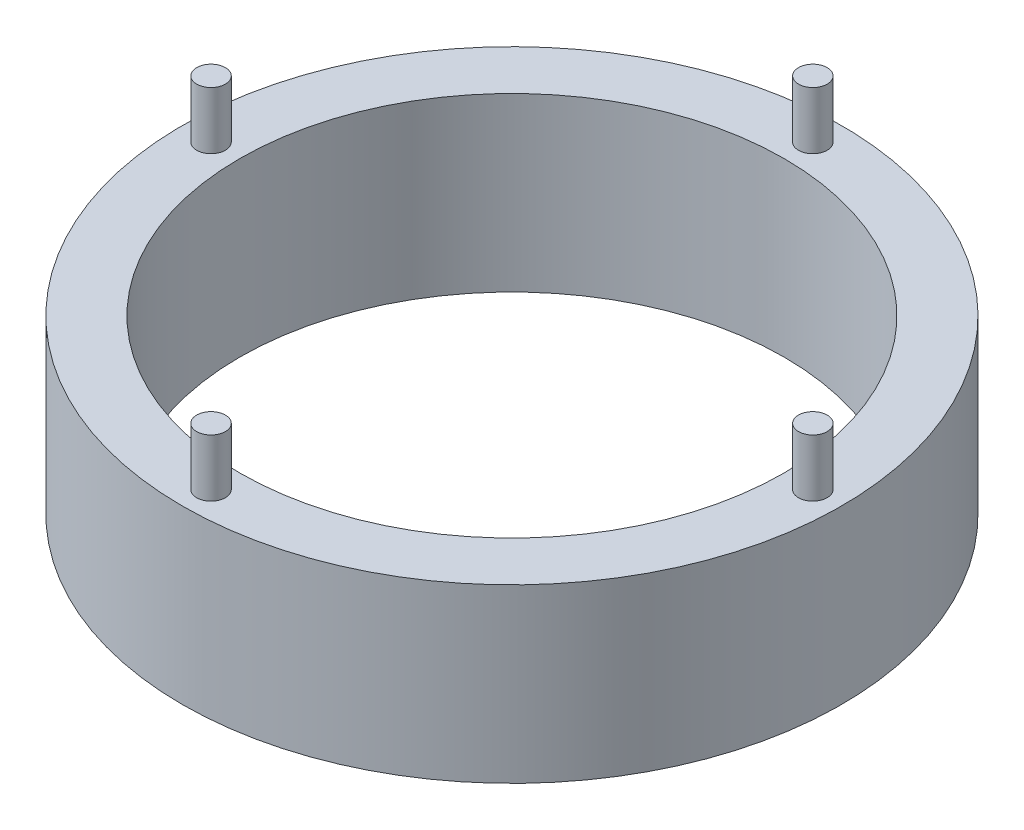
SolidWorks part; units mm, degrees
ref_plane "Plan de face" through (0, 0, 0) normal (0, 0, 1) x (1, 0, 0)
ref_plane "Plan de dessus" through (0, 0, 0) normal (0, 1, 0) x (1, 0, 0)
ref_plane "Plan de droite" through (0, 0, 0) normal (1, 0, 0) x (0, 0, -1)
sketch "Esquisse1" plane through (0, 0, 0) normal (0, 1, 0) x (1, 0, 0)
  circle A0 centre (0, 0) radius 47.5
  circle A1 centre (0, 0) radius 57.5
  dimension "D1" = 95
  dimension "D2" = 115
extrude "Boss.-Extru.1" add sketch "Esquisse1" along normal blind 30
sketch "Esquisse3" plane through (0, 0, 0) normal (0, 1, 0) x (1, 0, 0)
  circle A1 centre (0, 52.5) radius 2.5
  circle A2 centre (0, -52.5) radius 2.5
  circle A3 centre (-52.5, 0) radius 2.5
  circle A4 centre (52.5, 0) radius 2.5
extrude "Boss.-Extru.3" add sketch "Esquisse3" along normal blind 40 contours A2 | A3 | A1 | A4
sketch "Esquisse20" plane through (0, 0, 0) normal (0, 1, 0) x (1, 0, 0)
  circle A3 centre (0, -52.5) radius 2.5
  circle A4 centre (-52.5, 0) radius 2.5
  circle A5 centre (0, 52.5) radius 2.5
  circle A6 centre (52.5, 0) radius 2.5
sketch "Esquisse22" plane through (0, 0, 0) normal (0, 1, 0) x (1, 0, 0)
  circle A0 centre (0, 52.5) radius 2.5
sketch "Esquisse23" plane through (0, 0, 0) normal (0, 1, 0) x (1, 0, 0)
  circle A0 centre (-52.5, 0) radius 2.5
  circle A1 centre (0, -52.5) radius 2.5
  circle A2 centre (0, 0) radius 52.5 construction
  circle A3 centre (52.5, 0) radius 2.5
extrude "Enlèv. mat.-Extru.1" cut sketch "Esquisse23" along normal blind 10 contours A3
extrude "Enlèv. mat.-Extru.2" cut sketch "Esquisse22" along normal blind 10 contours A0
extrude "Enlèv. mat.-Extru.3" cut sketch "Esquisse20" along normal blind 10
